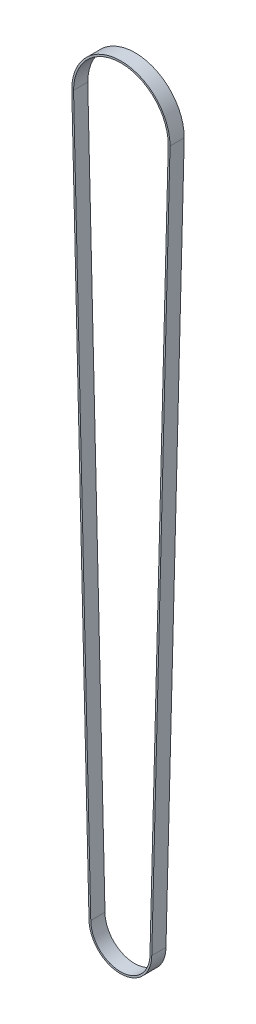
SolidWorks part; units mm, degrees
ref_plane "Front Plane" through (0, 0, 0) normal (0, 0, 1) x (1, 0, 0)
ref_plane "Top Plane" through (0, 0, 0) normal (0, 1, 0) x (1, 0, 0)
ref_plane "Right Plane" through (0, 0, 0) normal (1, 0, 0) x (0, 0, -1)
sketch "Sketch2" plane through (0, 0, 0) normal (0, 0, 1) x (1, 0, 0)
  line L0 (-63.5976, 166.1245) -> (-63.5976, -142.8755)
  line L1 (-22.0976, 166.1245) -> (-22.0976, -142.8755)
  line L4 (-62.8476, 166.1245) -> (-62.8476, -142.8755)
  line L6 (-22.8476, 166.1245) -> (-22.8476, -142.8755)
  arc A0 (-63.5976, -142.8755) -> (-22.0976, -142.8755) centre (-42.8476, -142.8755) ccw
  arc A1 (-63.5976, 166.1245) -> (-22.0976, 166.1245) centre (-42.8476, 166.1245) cw
  arc A2 (-62.8476, 166.1245) -> (-22.8476, 166.1245) centre (-42.8476, 166.1245) cw
  arc A3 (-62.8476, -142.8755) -> (-22.8476, -142.8755) centre (-42.8476, -142.8755) ccw
  dimension "D1" = 40
  dimension "D2" = 309
  dimension "D3" = 0.75
sketch "Sketch3" plane through (0, 0, 0) normal (0, 0, 1) x (1, 0, 0)
  line L0 (-168.0279, 409.3942) -> (-160.7476, 109.3942)
  line L1 (-135.7476, 109.3948) -> (-128.0279, 409.3942)
  line L2 (-168.7779, 409.385) -> (-161.4975, 109.385)
  line L3 (-134.9976, 109.385) -> (-127.2779, 409.3845)
  arc A0 (-168.0279, 409.3942) -> (-128.0279, 409.3942) centre (-148.0279, 409.3942) cw
  arc A1 (-135.7476, 109.3948) -> (-160.7476, 109.3942) centre (-148.2476, 109.3942) cw
  arc A2 (-134.9976, 109.385) -> (-161.4975, 109.385) centre (-148.2476, 109.3942) cw
  arc A3 (-168.7779, 409.385) -> (-127.2779, 409.3845) centre (-148.0279, 409.3942) cw
  dimension "D1" = 40
  dimension "D2" = 12.5
  dimension "D3" = 300
  dimension "D4" = 0.75
extrude "Boss-Extrude5" add sketch "Sketch3" along normal blind 6
